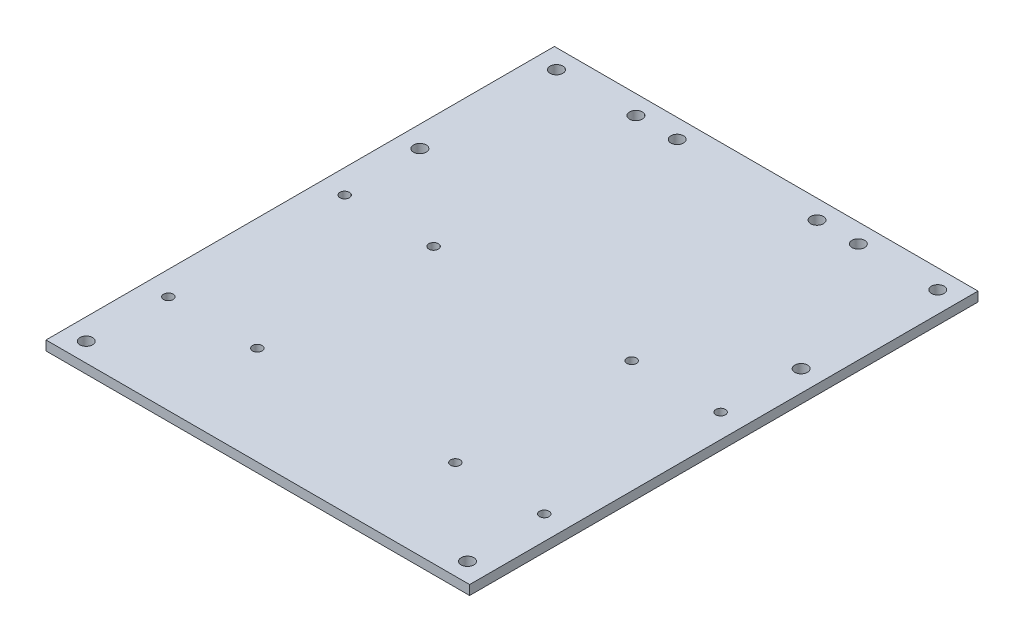
SolidWorks part; units mm, degrees
material "Acrylique (impact moyen-haut)"
ref_plane "Plan de face" through (0, 0, 0) normal (0, 0, 1) x (1, 0, 0)
ref_plane "Plan de dessus" through (0, 0, 0) normal (0, 1, 0) x (1, 0, 0)
ref_plane "Plan de droite" through (0, 0, 0) normal (1, 0, 0) x (0, 0, -1)
sketch "Esquisse1" plane through (0, 0, 0) normal (0, 1, 0) x (1, 0, 0)
  line L1 (-66.665, 80) -> (66.665, 80)
  line L2 (-66.665, 80) -> (-66.665, -80)
  line L3 (-66.665, -80) -> (66.665, -80)
  line L4 (66.665, 80) -> (66.665, -80)
  line L5 (-66.665, 80) -> (66.665, -80) construction
  line L6 (-66.665, -80) -> (66.665, 80) construction
  point P0 (0, 0)
  dimension "D1" = 133.33
  dimension "D2" = 160
extrude "Boss.-Extru.1" add sketch "Esquisse1" along normal blind 3
sketch "Esquisse2" plane through (0, 3, 0) normal (0, 1, 0) x (1, 0, 0)
  line L0 (-60, 80) -> (-60, 74) construction
  line L1 (66.665, 80) -> (-66.665, 80) construction
  line L2 (-66.665, 74) -> (-60, 74) construction
  line L3 (-66.665, 80) -> (-66.665, -80) construction
  line L4 (0, 0) -> (66.665, 0) construction
  line L5 (66.665, -80) -> (66.665, 80) construction
  line L6 (0, 0) -> (0, -80) construction
  line L7 (-66.665, -80) -> (66.665, -80) construction
  line L8 (-60, 74) -> (0, 74) construction
  line L9 (0, 74) -> (0, 0) construction
  circle A0 centre (-60, 74) radius 2
  circle A1 centre (60, 74) radius 2
  circle A2 centre (60, -74) radius 2
  circle A3 centre (-60, -74) radius 2
  dimension "D3" = 4
  dimension "D1" = 6
  dimension "D2" = 60
extrude "Enlèv. mat.-Extru.1" cut sketch "Esquisse2" against normal through all
sketch "Esquisse3" plane through (0, 3, 0) normal (0, 1, 0) x (1, 0, 0)
  line L0 (-60, 74) -> (-60, 31) construction
  line L1 (0, 0) -> (0, 80) construction
  line L2 (66.665, 80) -> (-66.665, 80) construction
  line L3 (-66.665, 80) -> (-66.665, 6.5) construction
  line L4 (-66.665, 80) -> (-66.665, -80) construction
  line L5 (-66.665, 6.5) -> (-59.165, 6.5) construction
  line L6 (-59.165, 6.5) -> (-31.165, 6.5) construction
  line L7 (-59.165, 6.5) -> (-59.165, -49) construction
  circle A0 centre (-60, 31) radius 2
  circle A1 centre (60, 31) radius 2
  circle A2 centre (-59.165, 6.5) radius 1.5
  circle A3 centre (-31.165, 6.5) radius 1.5
  circle A4 centre (-59.165, -49) radius 1.5
  circle A5 centre (-31.165, -49) radius 1.5
  circle A6 centre (31.165, -49) radius 1.5
  circle A7 centre (59.165, -49) radius 1.5
  circle A8 centre (59.165, 6.5) radius 1.5
  circle A9 centre (31.165, 6.5) radius 1.5
  circle A10 centre (-60, -74) radius 2 construction
  dimension "D2" = 4
  dimension "D5" = 3
  dimension "D7" = 3
  dimension "D1" = 105
  dimension "D3" = 73.5
  dimension "D4" = 7.5
  dimension "D6" = 28
  dimension "D8" = 55.5
extrude "Enlèv. mat.-Extru.2" cut sketch "Esquisse3" against normal through all
sketch "Esquisse4" plane through (0, 3, 0) normal (0, 1, 0) x (1, 0, 0)
  line L0 (-60, 74) -> (-35, 74) construction
  line L1 (60, 74) -> (35, 74) construction
  circle A0 centre (-35, 74) radius 2
  circle A3 centre (-60, 74) radius 2 construction
  circle A4 centre (35, 74) radius 2
  circle A5 centre (60, 74) radius 2 construction
  dimension "D2" = 25
  dimension "D1" = 25
extrude "Enlèv. mat.-Extru.3" cut sketch "Esquisse4" against normal blind 3.175
sketch "Esquisse5" plane through (0, 3, 0) normal (0, 1, 0) x (1, 0, 0)
  line L0 (-60, 74) -> (60, 74) construction
  line L1 (0, 74) -> (-22, 74) construction
  line L2 (0, 74) -> (0, 55.2576) construction
  circle A0 centre (-22, 74) radius 2
  circle A1 centre (-35, 74) radius 2 construction
  circle A2 centre (22, 74) radius 2
  dimension "D1" = 22
extrude "Enlèv. mat.-Extru.4" cut sketch "Esquisse5" against normal through all
